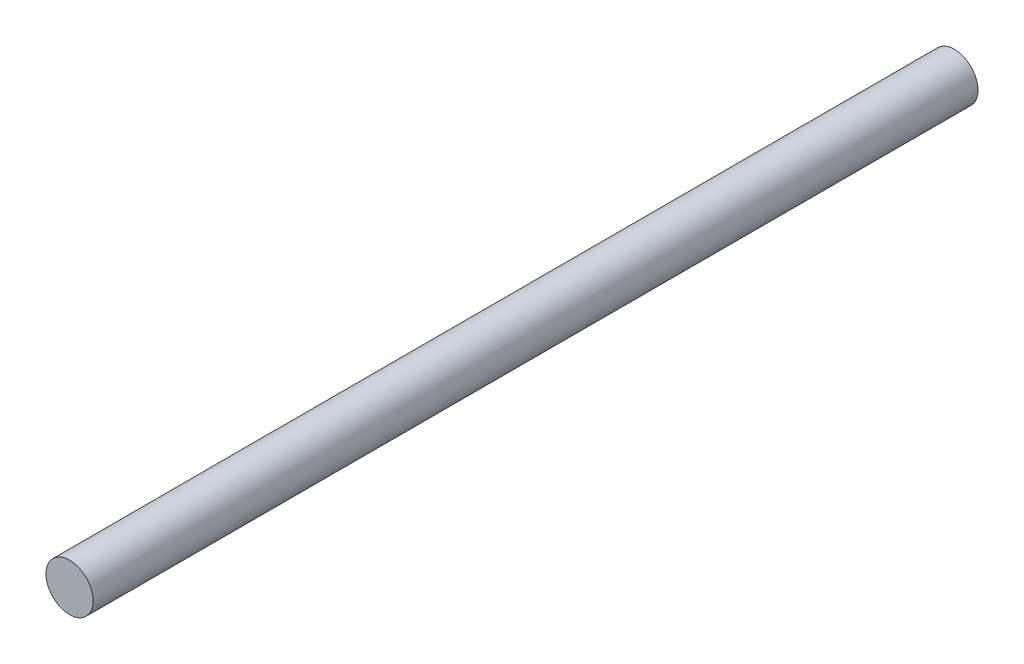
SolidWorks part; units mm, degrees
ref_plane "Plan de face" through (0, 0, 0) normal (0, 0, 1) x (1, 0, 0)
ref_plane "Plan de dessus" through (0, 0, 0) normal (0, 1, 0) x (1, 0, 0)
ref_plane "Plan de droite" through (0, 0, 0) normal (1, 0, 0) x (0, 0, -1)
sketch "Esquisse1" plane through (0, 0, 0) normal (0, 0, 1) x (1, 0, 0)
  circle A0 centre (0, 0) radius 4
  dimension "D1" = 8
extrude "Boss.-Extru.1" add sketch "Esquisse1" along normal blind 150
sketch "Esquisse2" plane through (0, 0, 150) normal (0, 0, 1) x (1, 0, 0)
  circle A0 centre (0, 0) radius 3.5
  dimension "D1" = 7
curve "Hélice/Spirale1" pitch 2 height 150 turns 75
